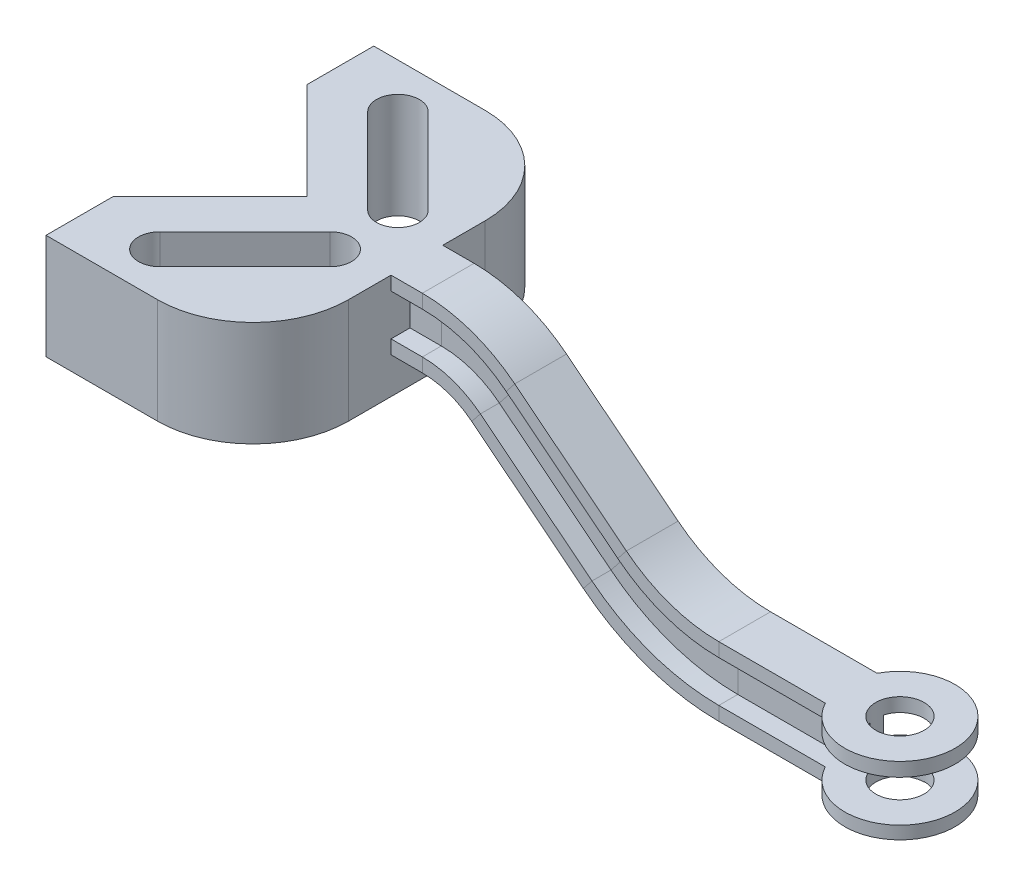
SolidWorks part; units mm, degrees
ref_plane "Front Plane" through (0, 0, 0) normal (0, 0, 1) x (1, 0, 0)
ref_plane "Top Plane" through (0, 0, 0) normal (0, 1, 0) x (1, 0, 0)
ref_plane "Right Plane" through (0, 0, 0) normal (1, 0, 0) x (0, 0, -1)
sketch "Sketch1" plane through (0, 0, 0) normal (0, 1, 0) x (1, 0, 0)
  line L0 (0, 140.4925) -> (140.4925, 0)
  line L1 (140.4925, 0) -> (300, 0)
  line L2 (0, 140.4925) -> (0, 237.5)
  line L3 (0, 237.5) -> (161.5, 237.5)
  line L4 (300, -99) -> (300, 99)
  line L5 (100, 172.5) -> (223.4326, 49.0674) construction
  line L6 (121.9203, 194.4203) -> (245.3529, 70.9878)
  line L7 (78.0797, 150.5797) -> (201.5122, 27.1471)
  line L8 (100, -172.5) -> (223.4326, -49.0674) construction
  line L9 (121.9203, -194.4203) -> (245.3529, -70.9878)
  line L10 (78.0797, -150.5797) -> (201.5122, -27.1471)
  line L11 (0, -237.5) -> (161.5, -237.5)
  line L12 (0, -140.4925) -> (0, -237.5)
  line L13 (0, -140.4925) -> (140.4925, 0)
  arc A0 (300, 99) -> (161.5, 237.5) centre (161.5, 99) ccw
  arc A1 (121.9203, 194.4203) -> (78.0797, 150.5797) centre (100, 172.5) ccw
  arc A2 (201.5122, 27.1471) -> (245.3529, 70.9878) centre (223.4326, 49.0674) ccw
  arc A3 (121.9203, -194.4203) -> (78.0797, -150.5797) centre (100, -172.5) cw
  arc A4 (201.5122, -27.1471) -> (245.3529, -70.9878) centre (223.4326, -49.0674) cw
  arc A5 (300, -99) -> (161.5, -237.5) centre (161.5, -99) cw
  point P9 (300, 237.5)
  point P12 (161.7163, 110.7837)
  point P18 (161.7163, -110.7837)
  point P28 (300, -237.5)
  dimension "D4" = 138.5
  dimension "D1" = 300
  dimension "D2" = 237.5
  dimension "D3" = 45
  dimension "D5" = 62
  dimension "D6" = 174.56
  dimension "D7" = 65
  dimension "D8" = 100
extrude "Boss-Extrude1" add sketch "Sketch1" along normal blind 152.5 contours A5 L4 L1 L13 L12 L11 L10 A4 L9 A3 | L4 A0 L3 L2 L0 L1 A2 L7 A1 L6
sketch "Sketch2" plane through (0, 0, 0) normal (0, 0, 1) x (1, 0, 0)
  line L0 (300, 152.5) -> (345.3563, 152.5)
  line L1 (479.3184, 105.6641) -> (641.0379, -23.1641)
  line L2 (775, -70) -> (1000, -70)
  line L3 (161.5, 0) -> (300, 0) construction
  arc A0 (479.3184, 105.6641) -> (345.3563, 152.5) centre (345.3563, -62.5) ccw
  arc A1 (775, -70) -> (641.0379, -23.1641) centre (775, 145) cw
  point P7 (420.5248, 152.5)
  dimension "D3" = 215
  dimension "D4" = 215
  dimension "D6" = 70
  dimension "D1" = 45.3563
  dimension "D2" = 700
  dimension "D5" = 225
sketch "Sketch3" plane through (300, 0, 0) normal (1, 0, 0) x (0, 0, -1)
  line L0 (-37.5, 152.5) -> (37.5, 152.5)
  line L1 (-99, 152.5) -> (99, 152.5) construction
  line L2 (37.5, 152.5) -> (37.5, 132.5)
  line L3 (37.5, 132.5) -> (10, 132.5)
  line L4 (10, 132.5) -> (10, 72.5)
  line L5 (10, 72.5) -> (37.5, 72.5)
  line L6 (37.5, 72.5) -> (37.5, 52.5)
  line L7 (37.5, 52.5) -> (-37.5, 52.5)
  line L9 (-37.5, 72.5) -> (-37.5, 52.5)
  line L10 (-10, 72.5) -> (-37.5, 72.5)
  line L11 (-10, 132.5) -> (-10, 72.5)
  line L12 (-37.5, 132.5) -> (-10, 132.5)
  line L13 (-37.5, 152.5) -> (-37.5, 132.5)
  dimension "D1" = 75
  dimension "D2" = 100
  dimension "D3" = 20
  dimension "D4" = 20
sketch "Sketch4" plane through (300, 0, 0) normal (1, 0, 0) x (0, 0, -1)
sweep "Sweep2" add profiles "Sketch3" path "Sketch2"
ref_plane "Plane2" through (0, 0, 0) normal (0, 0, -1) x (-1, 0, 0)
sketch "Sketch7" plane through (0, 0, 0) normal (0, 0, -1) x (-1, 0, 0)
  line L0 (-920, -70) -> (-920, -90)
  line L1 (-775, -70) -> (-1000, -70) construction
  line L2 (-775, -90) -> (-1000, -90) construction
  line L3 (-920, -90) -> (-990, -90)
  line L4 (-990, -90) -> (-990, -150)
  line L5 (-775, -150) -> (-1000, -150) construction
  line L6 (-990, -150) -> (-920.013, -150)
  line L7 (-920.013, -150) -> (-920.013, -168.559)
  line L8 (-920.013, -168.559) -> (-1000, -170)
  line L9 (-1000, -170) -> (-1000, -70)
  line L10 (-1000, -70) -> (-920, -70)
  line L11 (-1000, -43.9218) -> (-1000, -200.5071) construction
  dimension "D1" = 80
  dimension "D2" = 10
revolve "Revolve2" add sketch "Sketch7" angle 360 about L11
sketch "Sketch8" plane through (0, 0, 0) normal (0, 0, -1) x (-1, 0, 0)
sketch "Sketch9" plane through (0, -70, 0) normal (0, 1, 0) x (1, 0, 0)
  circle A0 centre (1000, 0) radius 35
  dimension "D1" = 70
extrude "Cut-Extrude1" cut sketch "Sketch9" against normal blind 152.5 contours A0
